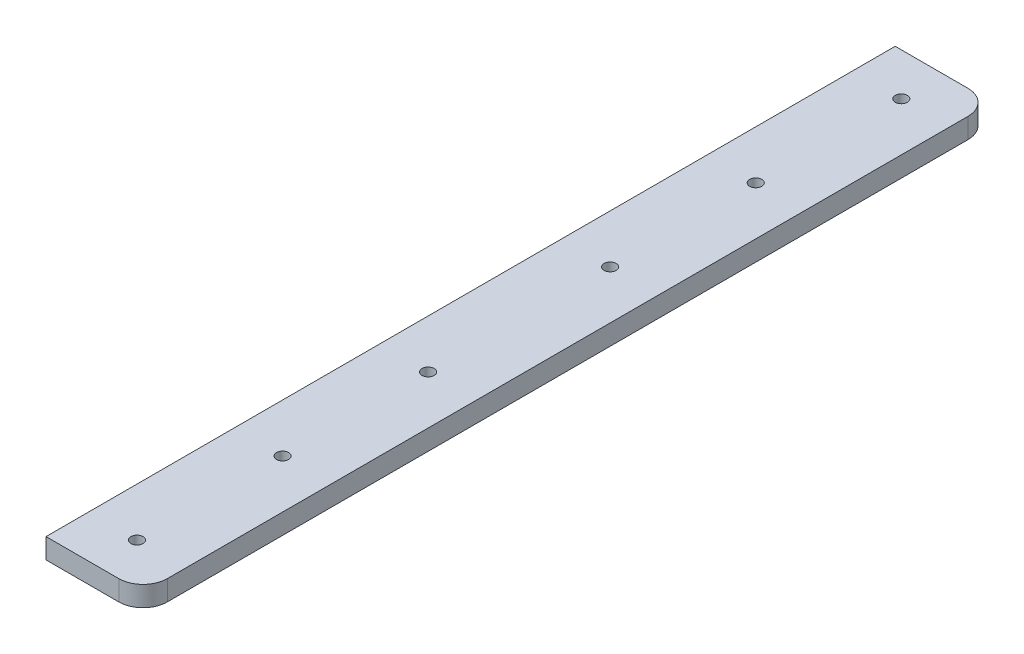
SolidWorks part; units mm, degrees
ref_plane "Front Plane" through (0, 0, 0) normal (0, 0, 1) x (1, 0, 0)
ref_plane "Top Plane" through (0, 0, 0) normal (0, 1, 0) x (1, 0, 0)
ref_plane "Right Plane" through (0, 0, 0) normal (1, 0, 0) x (0, 0, -1)
sketch "Sketch1" plane through (0, 0, 0) normal (0, 1, 0) x (1, 0, 0)
  line L4 (-12, -105) -> (-12, 105)
  line L13 (-12, 105) -> (6, 105)
  line L14 (12, 99) -> (12, -99)
  line L15 (6, -105) -> (-12, -105)
  line L16 (0, 105) -> (0, -105) construction
  arc A43 (6, -105) -> (12, -99) centre (6, -99) ccw
  arc A44 (12, 99) -> (6, 105) centre (6, 99) ccw
  circle A45 centre (0, -94.5) radius 1.5
  circle A46 centre (0, -58.5) radius 1.5
  circle A47 centre (0, -22.5) radius 1.5
  circle A71 centre (0, 94.5) radius 1.5
  circle A72 centre (0, 58.5) radius 1.5
  circle A73 centre (0, 22.5) radius 1.5
  point P0 (-9.9617, -105)
  dimension "D5" = 36
  dimension "D10" = 24
  dimension "D11" = 6
  dimension "D15" = 3
  dimension "D17" = 36
  dimension "D12" = 3
  dimension "D4" = 22.5
  dimension "D2" = 210
  dimension "D3" = 45
  dimension "D6" = 36
  dimension "D8" = 12
extrude "Boss-Extrude1" add sketch "Sketch1" along normal blind 5
